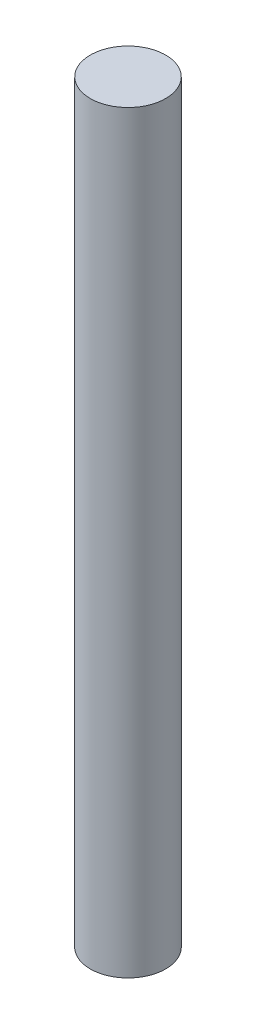
SolidWorks part; units mm, degrees
ref_plane "Alzado" through (0, 0, 0) normal (0, 0, 1) x (1, 0, 0)
ref_plane "Planta" through (0, 0, 0) normal (0, 1, 0) x (1, 0, 0)
ref_plane "Vista lateral" through (0, 0, 0) normal (1, 0, 0) x (0, 0, -1)
sketch "Croquis2" plane through (0, 0, 0) normal (0, 1, 0) x (1, 0, 0)
  circle A0 centre (0, 0) radius 10
  dimension "D1" = 20
extrude "Saliente-Extruir1" add sketch "Croquis2" along normal blind 200
